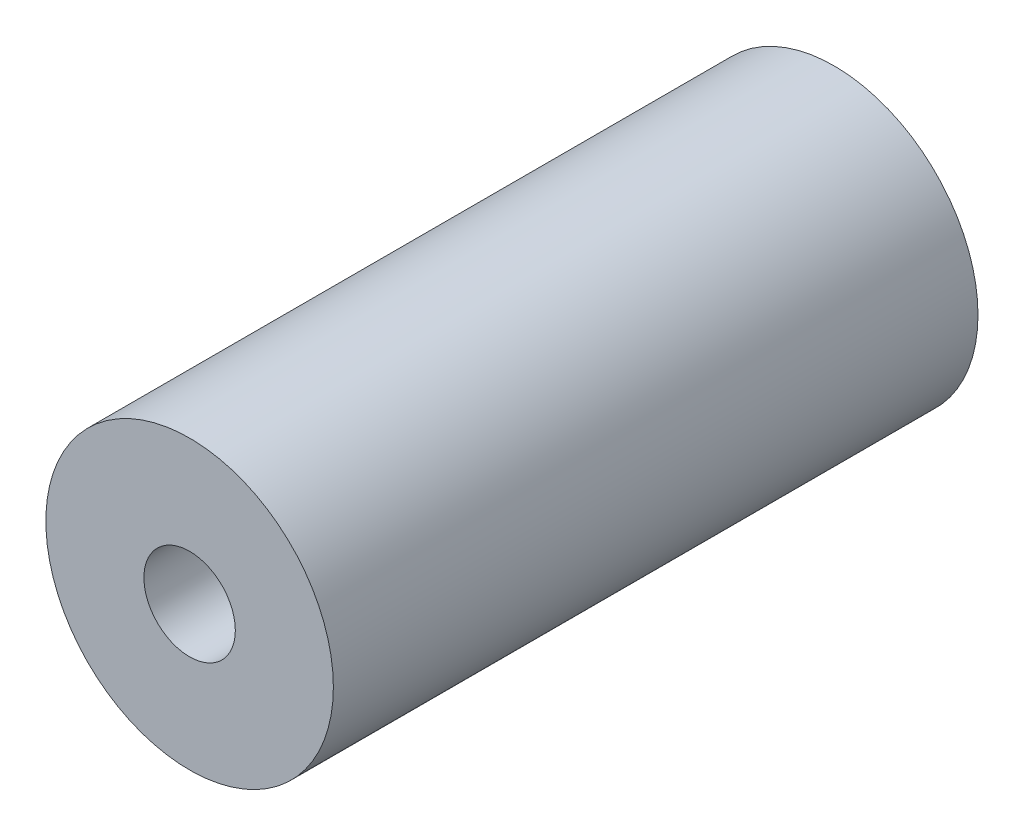
SolidWorks part; units mm, degrees
ref_plane "Front Plane" through (0, 0, 0) normal (0, 0, 1) x (1, 0, 0)
ref_plane "Top Plane" through (0, 0, 0) normal (0, 1, 0) x (1, 0, 0)
ref_plane "Right Plane" through (0, 0, 0) normal (1, 0, 0) x (0, 0, -1)
sketch "Sketch1" plane through (0, 0, 0) normal (0, 0, 1) x (1, 0, 0)
  circle A0 centre (0, 0) radius 6.35
  point P4 (0, 0)
  dimension "D1" = 12.7
extrude "Boss-Extrude1" add sketch "Sketch1" along normal blind 28.4734
sketch "Sketch2" plane through (0, 0, 28.4734) normal (0, 0, 1) x (1, 0, 0)
  point P0 (0, 0)
hole_wizard "#10-32 Tapped Hole2" positions "Sketch3" profile "Sketch4" tap size "#10-32" standard "ANSI Inch"
sketch "Sketch3" plane through (0, 0, 28.4734) normal (0, 0, 1) x (1, 0, 0)
  point P0 (0, 0)
sketch "Sketch4" plane through (0, 0, 28.4734) normal (1, 0, 0) x (0, -1, 0)
  line L0 (0, 0) -> (0, 11.1193)
  line L1 (0, 11.1193) -> (2.0193, 9.906)
  line L2 (2.0193, 9.906) -> (2.0193, 0)
  line L5 (2.0193, 0) -> (0, 0)
  line L10 (0, 11.1193) -> (-2.0193, 9.906) construction
  line L11 (0, -6.35) -> (0, 107.95) construction
  dimension "Tap Drill Dia." = 4.0386
  dimension "Tap Drill Depth" = 9.906
  dimension "Drill Angle" = 118
cosmetic thread "Hole Thread1" parameters "D1"=7.62, "D2"=4.826
hole_wizard "#10-32 Tapped Hole1" positions "Sketch7" profile "Sketch8" tap size "#10-32" standard "ANSI Inch"
sketch "Sketch7" plane through (0, 0, 0) normal (0, 0, -1) x (-1, 0, 0)
  point P0 (0, 0)
sketch "Sketch8" plane through (0, 0, 0) normal (1, 0, 0) x (0, 1, 0)
  line L0 (0, 0) -> (0, 13.1513)
  line L1 (0, 13.1513) -> (2.0193, 11.938)
  line L2 (2.0193, 11.938) -> (2.0193, 0)
  line L5 (2.0193, 0) -> (0, 0)
  line L10 (0, 13.1513) -> (-2.0193, 11.938) construction
  line L11 (0, -6.35) -> (0, 107.95) construction
  dimension "Tap Drill Dia." = 4.0386
  dimension "Tap Drill Depth" = 11.938
  dimension "Drill Angle" = 118
cosmetic thread "Hole Thread2" parameters "D1"=9.652, "D2"=4.826
